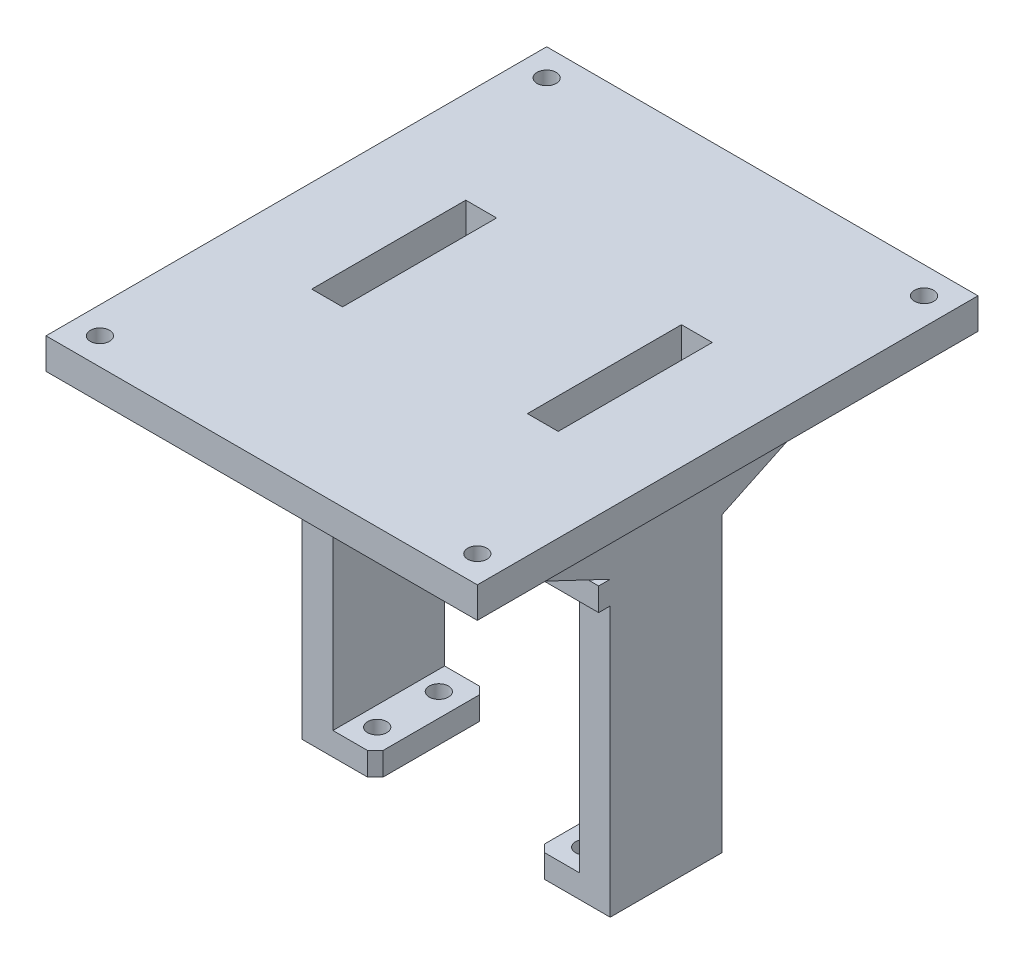
SolidWorks part; units mm, degrees
ref_plane "前视基准面" through (0, 0, 0) normal (0, 0, 1) x (1, 0, 0)
ref_plane "上视基准面" through (0, 0, 0) normal (0, 1, 0) x (1, 0, 0)
ref_plane "右视基准面" through (0, 0, 0) normal (1, 0, 0) x (0, 0, -1)
sketch "草图1" plane through (0, 0, 0) normal (0, 0, 1) x (1, 0, 0)
  line L0 (9.5, 3) -> (4, 3)
  line L8 (9.5, 0) -> (9.5, 3)
  line L13 (4, 35) -> (9.5, 35)
  line L14 (4, 3) -> (4, 35)
  line L15 (9.5, 35) -> (9.5, 38)
  line L16 (9.5, 38) -> (4, 38)
  line L17 (-8, 50) -> (0, 50)
  line L18 (4, 38) -> (4, 50)
  line L19 (4, 50) -> (36, 50)
  line L20 (40, 50) -> (48, 50)
  line L21 (-8, 50) -> (-8, 54)
  line L22 (-8, 54) -> (48, 54)
  line L23 (40, 0) -> (30.5, 0)
  line L24 (40, 50) -> (40, 0)
  line L26 (48, 50) -> (48, 54)
  line L27 (0, 50) -> (0, 0)
  line L29 (0, 0) -> (9.5, 0)
  line L32 (36, 38) -> (36, 50)
  line L34 (30.5, 38) -> (36, 38)
  line L35 (30.5, 35) -> (30.5, 38)
  line L36 (36, 3) -> (36, 35)
  line L37 (36, 35) -> (30.5, 35)
  line L38 (30.5, 0) -> (30.5, 3)
  line L39 (30.5, 3) -> (36, 3)
extrude "凸台-拉伸1" add sketch "草图1" along normal blind 65
sketch "草图2" plane through (0, 54, 0) normal (0, 1, 0) x (1, 0, 0)
  circle A2 centre (-4.5, -61.5) radius 1.25
  circle A3 centre (44.5, -61.5) radius 1.25
  circle A4 centre (44.5, -3.5) radius 1.25
  circle A5 centre (-4.5, -3.5) radius 1.25
extrude "切除-拉伸2" cut sketch "草图2" against normal up to next
sketch "草图10" plane through (0, 0, 0) normal (0, -1, 0) x (1, 0, 0)
  circle A1 centre (33.5, 36.5) radius 1.25
  circle A2 centre (33.5, 28.5) radius 1.25
  circle A3 centre (6.5, 28.5) radius 1.25
  circle A4 centre (6.5, 36.5) radius 1.25
extrude "切除-拉伸4" cut sketch "草图10" against normal up to surface (38 mm away) up to face at (6.75, 38, 32.5)
sketch "草图20" plane through (0, 0, 0) normal (-1, 0, 0) x (0, 0, 1)
  line L4 (0, 50) -> (0, 0)
  line L5 (65, 50) -> (65, 0)
  line L6 (25.25, 0) -> (25.25, 38)
  line L7 (25.25, 38) -> (0, 50)
  line L8 (0, 0) -> (25.25, 0)
  line L9 (65, 0) -> (0, 0) construction
  line L10 (39.75, 38) -> (65, 50)
  line L11 (39.75, 0) -> (39.75, 38)
  line L12 (65, 0) -> (39.75, 0)
extrude "切除-拉伸8" cut sketch "草图20" against normal through all
sketch "草图21" plane through (0, 0, 0) normal (0, -1, 0) x (1, 0, 0)
  line L0 (30.5, 38.75) -> (31.5, 39.75)
  line L1 (30.5, 39.75) -> (31.5, 39.75)
  line L2 (30.5, 39.75) -> (30.5, 38.75)
  line L5 (30.5, 26.25) -> (31.5, 25.25)
  line L6 (30.5, 25.25) -> (31.5, 25.25)
  line L7 (30.5, 25.25) -> (30.5, 26.25)
extrude "切除-拉伸9" cut sketch "草图21" against normal up to surface (38 mm away) up to face at (33.5, 38, 27.25)
sketch "草图22" plane through (0, 0, 0) normal (0, -1, 0) x (-1, 0, 0)
  line L0 (-8.5, -39.75) -> (-9.5, -38.75)
  line L5 (-9.5, -39.75) -> (-8.5, -39.75)
  line L6 (-9.5, -39.75) -> (-9.5, -38.75)
  line L9 (-9.5, -25.25) -> (-8.5, -25.25)
  line L10 (-9.5, -25.25) -> (-9.5, -26.25)
  line L13 (-8.5, -25.25) -> (-9.5, -26.25)
extrude "切除-拉伸10" cut sketch "草图22" against normal up to surface (38 mm away) up to face at (6.5, 38, 35.25)
sketch "草图25" plane through (0, 0, 39.75) normal (0, 0, 1) x (1, 0, 0)
  line L1 (0, 38) -> (8.5, 38)
  line L2 (0, 38) -> (0, 35)
  line L3 (0, 35) -> (8.5, 35)
  line L4 (8.5, 38) -> (8.5, 35)
extrude "凸台-拉伸2" add sketch "草图25" along normal blind 1.5
sketch "草图26" plane through (0, 0, 39.75) normal (0, 0, 1) x (1, 0, 0)
  line L1 (40, 38) -> (31.5, 38)
  line L2 (40, 38) -> (40, 35)
  line L3 (40, 35) -> (31.5, 35)
  line L4 (31.5, 38) -> (31.5, 35)
extrude "凸台-拉伸3" add sketch "草图26" along normal blind 1.5
sketch "草图27" plane through (0, 54, 0) normal (0, 1, 0) x (1, 0, 0)
  line L3 (4, -32.5) -> (4, -22.5)
  line L4 (4, -22.5) -> (8, -22.5)
  line L5 (8, -22.5) -> (8, -42.5)
  line L6 (8, -42.5) -> (4, -42.5)
  line L7 (4, -42.5) -> (4, -32.5)
  line L8 (36, -32.5) -> (36, -22.5)
  line L9 (36, -22.5) -> (32, -22.5)
  line L10 (32, -22.5) -> (32, -42.5)
  line L11 (32, -42.5) -> (36, -42.5)
  line L12 (36, -42.5) -> (36, -32.5)
extrude "切除-拉伸11" cut sketch "草图27" against normal up to next
